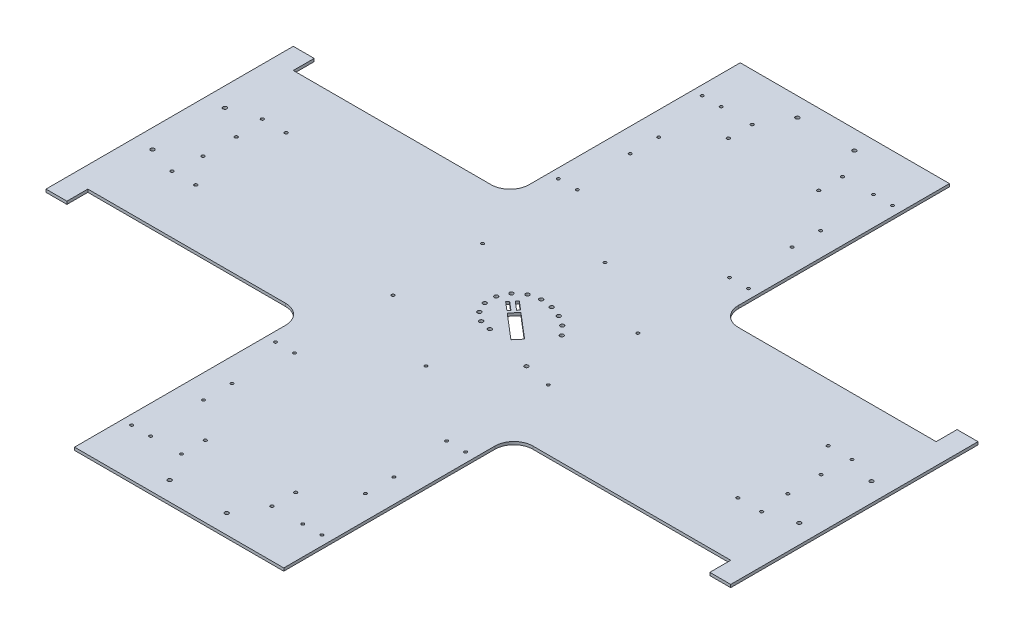
SolidWorks part; units mm, degrees
ref_plane "Front Plane" through (0, 0, 0) normal (0, 0, 1) x (1, 0, 0)
ref_plane "Top Plane" through (0, 0, 0) normal (0, 1, 0) x (1, 0, 0)
ref_plane "Right Plane" through (0, 0, 0) normal (1, 0, 0) x (0, 0, -1)
sketch "Sketch1" plane through (0, 0, 0) normal (0, 1, 0) x (1, 0, 0)
  line L0 (-110, 350) -> (-110, 108)
  line L1 (-110, 108) -> (-338, 108)
  line L2 (-338, 108) -> (-338, 130)
  line L3 (-338, 130) -> (-360, 130)
  line L4 (-360, 130) -> (-360, -130)
  line L5 (-360, 0) -> (1003.1457, 0) construction
  line L6 (0, 350) -> (0, -620.7989) construction
  line L7 (-338, -130) -> (-360, -130)
  line L8 (-338, -108) -> (-338, -130)
  line L9 (-110, -108) -> (-338, -108)
  line L10 (-110, 350) -> (110, 350)
  line L11 (-110, -350) -> (-110, -108)
  line L12 (-110, -350) -> (110, -350)
  line L13 (110, -350) -> (110, -108)
  line L14 (110, -108) -> (338, -108)
  line L15 (338, -108) -> (338, -130)
  line L16 (338, -130) -> (360, -130)
  line L17 (360, 130) -> (360, -130)
  line L18 (338, 130) -> (360, 130)
  line L19 (338, 108) -> (338, 130)
  line L20 (110, 108) -> (338, 108)
  line L21 (110, 350) -> (110, 108)
  point P17 (0, -350)
  dimension "D1" = 110
  dimension "D2" = 22
  dimension "D3" = 22
  dimension "D4" = 242
  dimension "D5" = 130
  dimension "D6" = 250
  dimension "D7" = 110
  dimension "D8" = 108
extrude "Boss-Extrude1" add sketch "Sketch1" along normal blind 3
sketch "Sketch2" plane through (0, 3, 0) normal (0, 1, 0) x (1, 0, 0)
  line L0 (360, -130) -> (360, 130) construction
  line L2 (338, 108) -> (110, 108) construction
  line L4 (0, 107.9437) -> (0, -458.275) construction
  line L5 (110, 108) -> (110, 350) construction
  line L6 (110, 350) -> (-110, 350) construction
  line L7 (-540.1841, 0) -> (-80.3508, 0) construction
  circle A0 centre (310, 47.5) radius 1.6
  circle A1 centre (285, 47.5) radius 1.6
  circle A2 centre (307.5, 17.5) radius 1.6
  circle A3 centre (307.5, -17.5) radius 1.6
  circle A4 centre (310, -47.5) radius 1.6
  circle A5 centre (285, -47.5) radius 1.6
  circle A6 centre (-285, -47.5) radius 1.6
  circle A7 centre (-310, -47.5) radius 1.6
  circle A8 centre (-307.5, -17.5) radius 1.6
  circle A9 centre (-307.5, 17.5) radius 1.6
  circle A10 centre (-285, 47.5) radius 1.6
  circle A11 centre (-310, 47.5) radius 1.6
  circle A13 centre (47.5, 300) radius 1.6
  circle A15 centre (47.5, 275) radius 1.6
  circle A16 centre (-47.5, 275) radius 1.6
  circle A17 centre (-47.5, 300) radius 1.6
  circle A18 centre (-47.5, -300) radius 1.6
  circle A19 centre (-47.5, -275) radius 1.6
  circle A20 centre (47.5, -275) radius 1.6
  circle A21 centre (47.5, -300) radius 1.6
  dimension "D1" = 3.2
  dimension "D2" = 3.2
  dimension "D3" = 3.2
  dimension "D4" = 3.2
  dimension "D5" = 3.2
  dimension "D6" = 3.2
  dimension "D15" = 3.2
  dimension "D16" = 3.2
  dimension "D7" = 50
  dimension "D8" = 25
  dimension "D9" = 95
  dimension "D10" = 35
  dimension "D11" = 60.5
  dimension "D12" = 90.5
  dimension "D13" = 52.5
  dimension "D14" = 110
  dimension "D17" = 50
  dimension "D18" = 25
  dimension "D19" = 62.5
  dimension "D20" = 108
extrude "Cut-Extrude1" cut sketch "Sketch2" against normal through all
sketch "Sketch3" plane through (0, 3, 0) normal (0, 1, 0) x (1, 0, 0)
  line L0 (360, -130) -> (360, 130) construction
  line L1 (338, 108) -> (110, 108) construction
  line L2 (-553.4456, 0) -> (-91.4299, 0) construction
  line L3 (0, 286.895) -> (0, -255.8046) construction
  line L4 (110, 108) -> (110, 350) construction
  line L5 (110, 350) -> (-110, 350) construction
  line L6 (-110, 350) -> (-110, 108) construction
  circle A0 centre (340, 38) radius 2
  circle A2 centre (340, -38) radius 2
  circle A3 centre (-340, -38) radius 2
  circle A4 centre (-340, 38) radius 2
  circle A5 centre (-30, 330) radius 2
  circle A7 centre (30, 330) radius 2
  circle A8 centre (30, -330) radius 2
  circle A9 centre (-30, -330) radius 2
  dimension "D1" = 4
  dimension "D6" = 4
  dimension "D7" = 80
  dimension "D2" = 20
  dimension "D3" = 70
  dimension "D4" = 108
  dimension "D5" = 110
  dimension "D8" = 20
extrude "Cut-Extrude2" cut sketch "Sketch3" against normal through all
sketch "Sketch4" plane through (0, 3, 0) normal (0, 1, 0) x (1, 0, 0)
  line L0 (0.8085, 29.8301) -> (-10.8593, 27.1789) construction
  line L1 (-10.8593, 27.1789) -> (-20.2814, 19.6888) construction
  line L2 (-20.2814, 19.6888) -> (-25.5122, 8.8484) construction
  line L3 (-25.5122, 8.8484) -> (-25.5122, -3.1881) construction
  line L4 (-25.5122, -3.1881) -> (-20.2814, -14.0285) construction
  line L5 (-20.2814, -14.0285) -> (-10.8593, -21.5186) construction
  line L6 (-10.8593, -21.5186) -> (0.8815, -24.1698) construction
  line L7 (0.8085, 29.8301) -> (13.3461, 28.3304) construction
  line L8 (13.3461, 28.3304) -> (25.203, 23.9881) construction
  line L9 (25.203, 23.9881) -> (35.7602, 17.0608) construction
  line L10 (35.7602, 17.0608) -> (44.4635, 7.9124) construction
  line L11 (44.4635, 7.9124) -> (53.9283, -38.7532) construction
  line L12 (0.8085, 2.8301) -> (0.8085, 97.0801) construction
  line L13 (0.8085, 2.8301) -> (0.8085, 97.0801) construction
  line L14 (0.8085, 2.8301) -> (82.4314, 49.9551) construction
  line L15 (-4.5918, -0.4234) -> (21.6669, -22.8005)
  line L16 (21.6669, -22.8005) -> (28.2827, -15.037)
  line L17 (-4.5918, -0.4234) -> (2.0241, 7.3401)
  line L18 (2.0241, 7.3401) -> (28.2827, -15.037)
  line L19 (-6.8751, 1.5225) -> (-4.9293, 3.8058)
  line L20 (-4.9293, 3.8058) -> (-14.0627, 11.5892)
  line L21 (-14.0627, 11.5892) -> (-16.0085, 9.3058)
  line L22 (-16.0085, 9.3058) -> (-6.8751, 1.5225)
  line L23 (2.0241, 7.3401) -> (0.8085, 2.8301) construction
  line L24 (-2.2051, 7.0025) -> (-0.2593, 9.2859)
  line L25 (-0.2593, 9.2859) -> (-9.3927, 17.0692)
  line L26 (-9.3927, 17.0692) -> (-11.3385, 14.7859)
  line L27 (-11.3385, 14.7859) -> (-2.2051, 7.0025)
  line L28 (0.8085, 2.8301) -> (48.4037, 2.8301) construction
  line L29 (0.8085, 2.8301) -> (0.8085, -17.1699) construction
  circle A0 centre (0.8085, 29.8301) radius 2
  circle A1 centre (13.3461, 28.3304) radius 2
  circle A2 centre (25.203, 23.9881) radius 2
  circle A3 centre (35.7602, 17.0608) radius 2
  circle A4 centre (44.4635, 7.9124) radius 2
  circle A5 centre (53.9283, -38.7532) radius 2
  circle A6 centre (0.8085, 2.8301) radius 135 construction
  circle A7 centre (-10.8593, 27.1789) radius 2
  circle A8 centre (-20.2814, 19.6888) radius 2
  circle A9 centre (-25.5122, 8.8484) radius 2
  circle A10 centre (-25.5122, -3.1881) radius 2
  circle A11 centre (-20.2814, -14.0285) radius 2
  circle A12 centre (-10.8593, -21.5186) radius 2
  circle A13 centre (0.8815, -24.1698) radius 2
  circle A14 centre (0.8085, 2.8301) radius 27 construction
  circle A15 centre (0.8085, 2.8301) radius 28.4158 construction
  circle A16 centre (0.8085, 2.8301) radius 32.2916 construction
  circle A17 centre (0.8085, 2.8301) radius 37.7377 construction
  circle A18 centre (0.8085, 2.8301) radius 43.9498 construction
  circle A19 centre (0.8085, 2.8301) radius 67.4602 construction
  circle A20 centre (0.8085, 2.8301) radius 94.25 construction
  circle A21 centre (0.8085, 97.0801) radius 1.5
  circle A22 centre (82.4314, 49.9551) radius 1.5
  circle A23 centre (82.4314, -44.2949) radius 1.5
  circle A24 centre (0.8085, -91.4199) radius 1.5
  circle A25 centre (-80.8144, -44.2949) radius 1.5
  circle A26 centre (-80.8144, 49.9551) radius 1.5
  point P32 (0.8085, 2.8301)
  dimension "D1" = 4
  dimension "D2" = 270
  dimension "D3" = 54
  dimension "D12" = 188.5
  dimension "D13" = 3
  dimension "D4" = 11.9653
  dimension "D5" = 12.627
  dimension "D6" = 47.6157
  dimension "D8" = 60.7074
  dimension "D9" = 70.0293
  dimension "D10" = 81.6875
  dimension "D14" = 60
  dimension "D15" = 34.5
  dimension "D16" = 10.2
  dimension "D17" = 12
  dimension "D18" = 3
  dimension "D19" = 3
  dimension "D20" = 4.6709
  dimension "D21" = 3
  dimension "D22" = 20
  dimension "D23" = 130.437
  dimension "D24" = 5.4003
extrude "Cut-Extrude3" cut sketch "Sketch4" against normal blind 10
sketch "Sketch5" plane through (0, 3, 0) normal (0, 1, 0) x (1, 0, 0)
  line L0 (110, 350) -> (-110, 350) construction
  line L1 (110, 108) -> (110, 350) construction
  line L2 (0, 224.365) -> (185.6725, 224.365) construction
  line L3 (90, 361.0488) -> (90, 126.2188) construction
  line L4 (0, 375.894) -> (0, 88.4107) construction
  line L5 (349.7475, 0) -> (-242.2654, 0) construction
  circle A0 centre (80, 300) radius 1.5
  circle A1 centre (80, 148.73) radius 1.5
  circle A2 centre (85.11, 239.365) radius 1.5
  circle A3 centre (85.11, 209.365) radius 1.5
  circle A4 centre (100, 148.73) radius 1.5
  circle A5 centre (100, 300) radius 1.5
  circle A6 centre (-100, 300) radius 1.5
  circle A7 centre (-100, 148.73) radius 1.5
  circle A8 centre (-85.11, 209.365) radius 1.5
  circle A9 centre (-85.11, 239.365) radius 1.5
  circle A10 centre (-80, 148.73) radius 1.5
  circle A11 centre (-80, 300) radius 1.5
  circle A12 centre (-80, -300) radius 1.5
  circle A13 centre (-80, -148.73) radius 1.5
  circle A14 centre (-85.11, -239.365) radius 1.5
  circle A15 centre (-85.11, -209.365) radius 1.5
  circle A16 centre (-100, -148.73) radius 1.5
  circle A17 centre (-100, -300) radius 1.5
  circle A18 centre (100, -300) radius 1.5
  circle A19 centre (100, -148.73) radius 1.5
  circle A20 centre (85.11, -209.365) radius 1.5
  circle A21 centre (85.11, -239.365) radius 1.5
  circle A22 centre (80, -148.73) radius 1.5
  circle A23 centre (80, -300) radius 1.5
  dimension "D1" = 3
  dimension "D2" = 3
  dimension "D6" = 3
  dimension "D7" = 3
  dimension "D3" = 151.27
  dimension "D4" = 50
  dimension "D5" = 5.11
  dimension "30" = 30
  dimension "D8" = 30
  dimension "D9" = 75.635
  dimension "D10" = 15
  dimension "D11" = 10
extrude "Cut-Extrude4" cut sketch "Sketch5" against normal blind 10
fillet "Fillet1" radius 20 4 edges at (110, 1.5, -108) (-110, 1.5, -108) (-110, 1.5, 108) (110, 1.5, 108)
equation "\"M3\"= 3.2mm"
equation "\"D1@Sketch2\"=\"M3\""
equation "\"D2@Sketch2\"=\"M3\""
equation "\"D3@Sketch2\"=\"M3\""
equation "\"D4@Sketch2\"=\"M3\""
equation "\"D5@Sketch2\"=\"M3\""
equation "\"D6@Sketch2\"=\"M3\""
equation "\"D15@Sketch2\"=\"M3\""
equation "\"D16@Sketch2\"=\"M3\""
